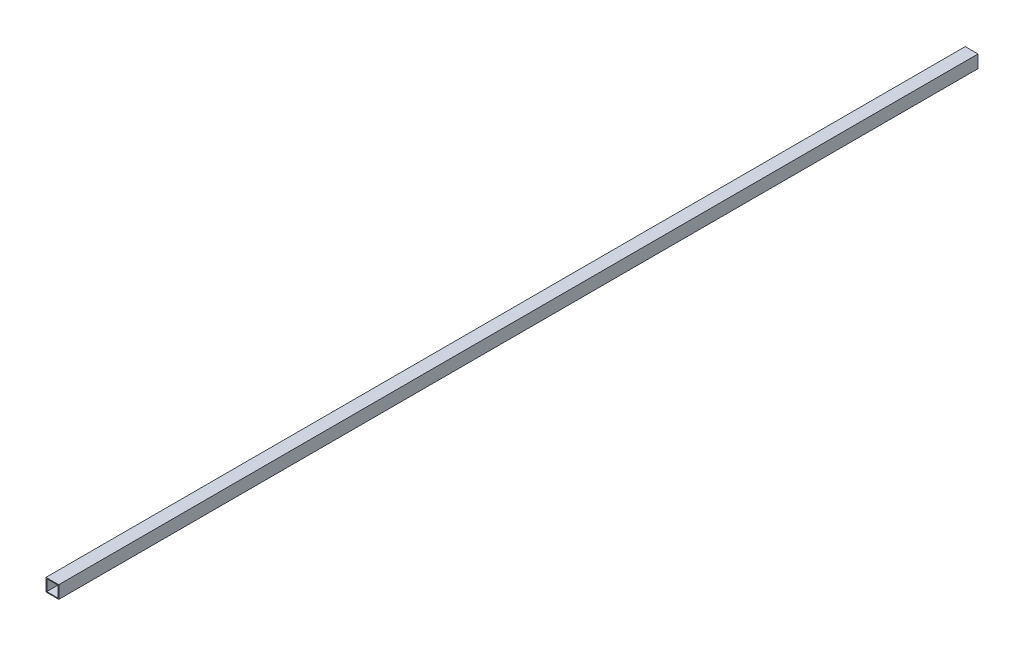
SolidWorks part; units mm, degrees
ref_plane "Front Plane" through (0, 0, 0) normal (0, 0, 1) x (1, 0, 0)
ref_plane "Top Plane" through (0, 0, 0) normal (0, 1, 0) x (1, 0, 0)
ref_plane "Right Plane" through (0, 0, 0) normal (1, 0, 0) x (0, 0, -1)
sketch "Sketch1" plane through (0, 0, 0) normal (0, 0, 1) x (1, 0, 0)
  line L1 (-25.4, -25.4) -> (25.4, -25.4)
  line L2 (-25.4, -25.4) -> (-25.4, 25.4)
  line L3 (-25.4, 25.4) -> (25.4, 25.4)
  line L4 (25.4, -25.4) -> (25.4, 25.4)
  line L5 (-25.4, -25.4) -> (25.4, 25.4) construction
  line L6 (-25.4, 25.4) -> (25.4, -25.4) construction
  point P0 (0, 0)
  dimension "D1" = 50.8
  dimension "D2" = 50.8
extrude "Boss-Extrude1" add sketch "Sketch1" along normal blind 3657.6
shell "Shell1" thickness 3.175
